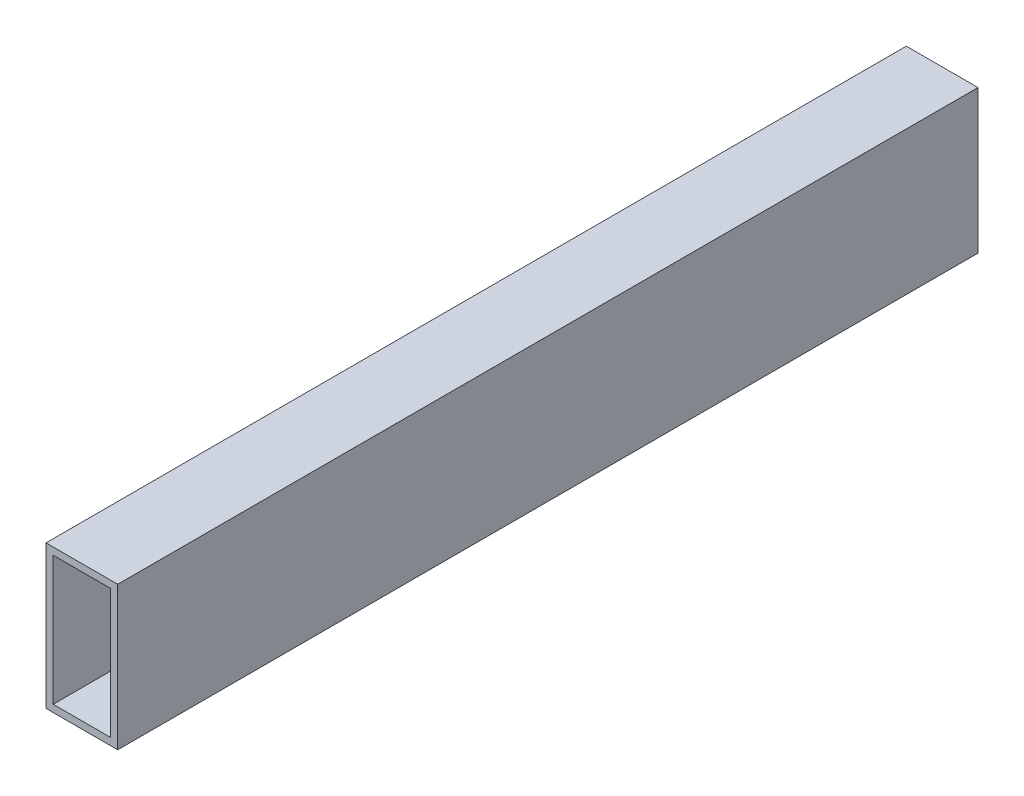
SolidWorks part; units mm, degrees
ref_plane "Front Plane" through (0, 0, 0) normal (0, 0, 1) x (1, 0, 0)
ref_plane "Top Plane" through (0, 0, 0) normal (0, 1, 0) x (1, 0, 0)
ref_plane "Right Plane" through (0, 0, 0) normal (1, 0, 0) x (0, 0, -1)
sketch "Sketch1" plane through (0, 0, 0) normal (0, 0, 1) x (1, 0, 0)
  line L1 (-12.5, 25) -> (12.5, 25)
  line L2 (-12.5, 25) -> (-12.5, -25)
  line L3 (-12.5, -25) -> (12.5, -25)
  line L4 (12.5, 25) -> (12.5, -25)
  line L5 (-12.5, 25) -> (12.5, -25) construction
  line L6 (-12.5, -25) -> (12.5, 25) construction
  line L7 (-10, 22.5) -> (10, 22.5)
  line L8 (-10, 22.5) -> (-10, -22.5)
  line L9 (-10, -22.5) -> (10, -22.5)
  line L10 (10, 22.5) -> (10, -22.5)
  line L11 (-10, 22.5) -> (10, -22.5) construction
  line L12 (-10, -22.5) -> (10, 22.5) construction
  point P0 (0, 0)
  point P6 (0, 0)
  point P11 (0.8875, -2.3029)
  dimension "D1" = 50
  dimension "D2" = 25
  dimension "D3" = 2.5
  dimension "D4" = 2.5
extrude "Boss-Extrude1" add sketch "Sketch1" along normal blind 300
